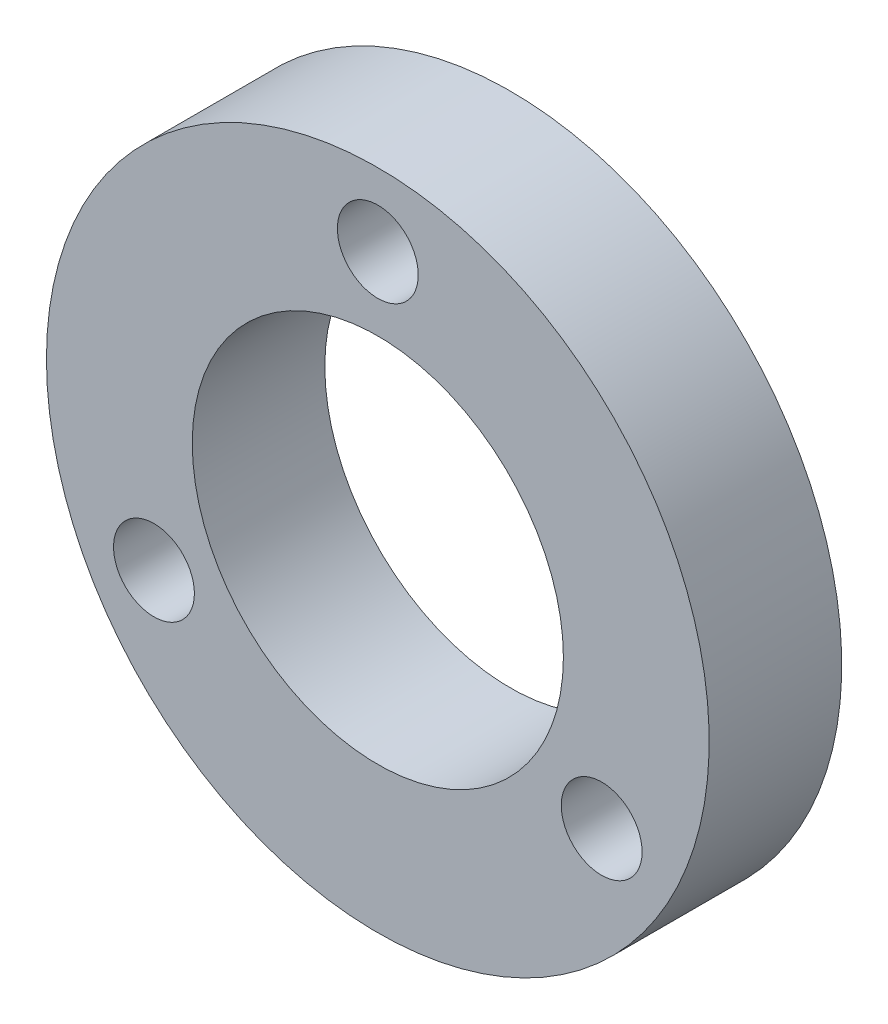
SolidWorks part; units mm, degrees
ref_plane "Front Plane" through (0, 0, 0) normal (0, 0, 1) x (1, 0, 0)
ref_plane "Top Plane" through (0, 0, 0) normal (0, 1, 0) x (1, 0, 0)
ref_plane "Right Plane" through (0, 0, 0) normal (1, 0, 0) x (0, 0, -1)
sketch "Sketch1" plane through (0, 0, 0) normal (0, 0, 1) x (1, 0, 0)
  circle A0 centre (0, 0) radius 12.5
  circle A1 centre (0, 0) radius 7
  dimension "D1" = 25
  dimension "D2" = 14
extrude "Boss-Extrude1" add sketch "Sketch1" along normal blind 5
sketch "Sketch2" plane through (0, 0, 5) normal (0, 0, 1) x (1, 0, 0)
  circle A1 centre (0, 9.75) radius 1.525
  circle A2 centre (8.4437, -4.875) radius 1.525
  circle A3 centre (-8.4437, -4.875) radius 1.525
  point P12 (0, 0)
  dimension "D2" = 3.05
  dimension "D3" = 3
extrude "Cut-Extrude1" cut sketch "Sketch2" against normal up to next
